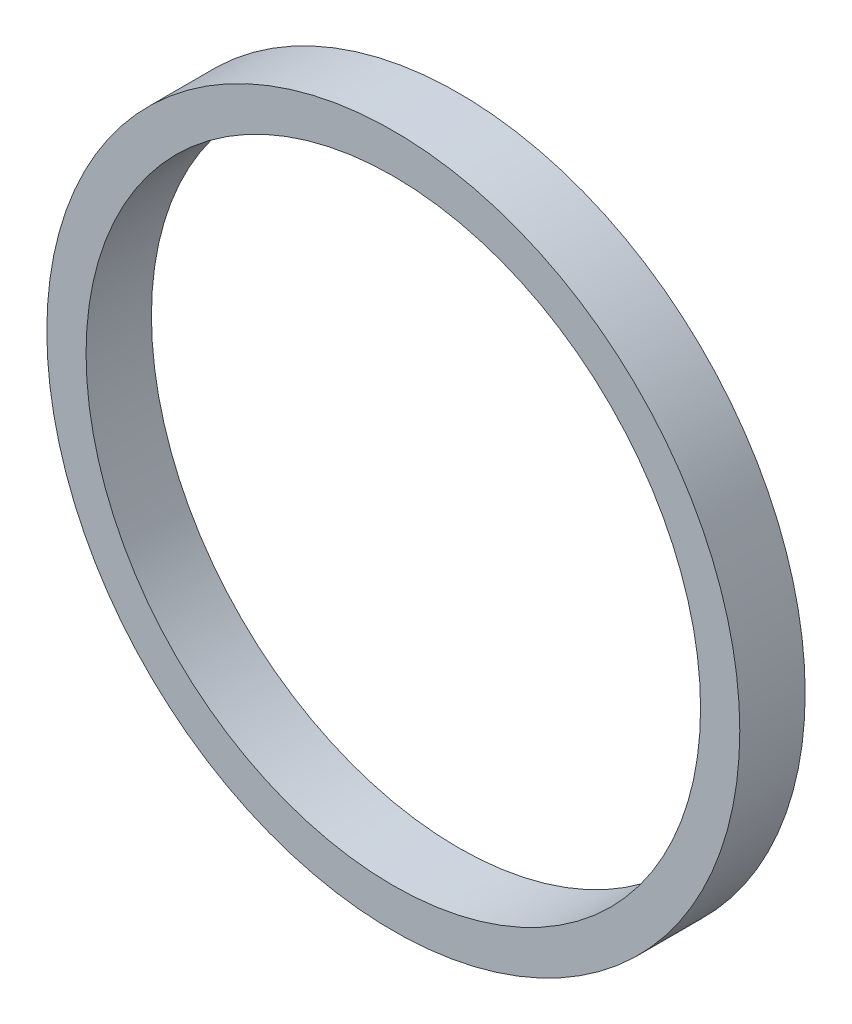
SolidWorks part; units mm, degrees
ref_plane "Front Plane" through (0, 0, 0) normal (0, 0, 1) x (1, 0, 0)
ref_plane "Top Plane" through (0, 0, 0) normal (0, 1, 0) x (1, 0, 0)
ref_plane "Right Plane" through (0, 0, 0) normal (1, 0, 0) x (0, 0, -1)
sketch "Sketch2" plane through (0, 0, 0) normal (0, 0, 1) x (1, 0, 0)
  circle A0 centre (0, 0) radius 15.9
  dimension "D1" = 31.8
extrude "Extrude-Thin1" add sketch "Sketch2" along normal blind 3 thin thin type one direction reverse wall 1.8
